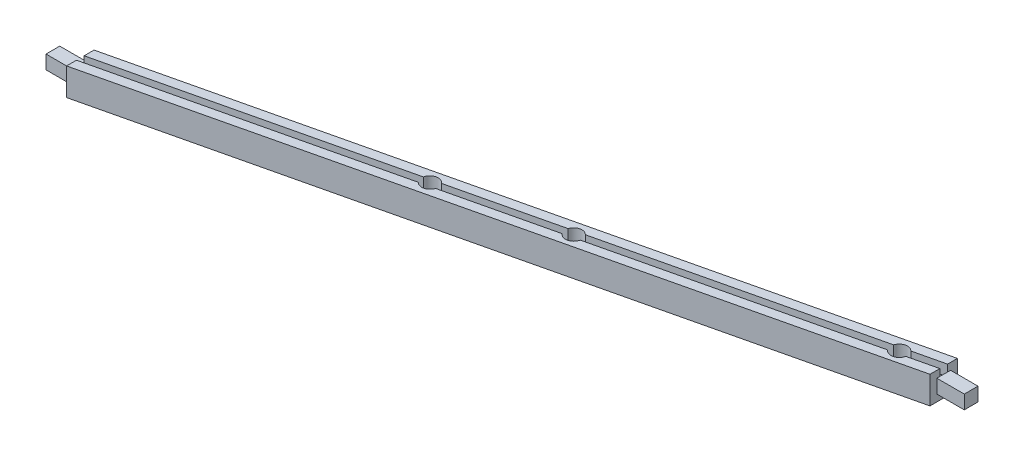
SolidWorks part; units mm, degrees
ref_plane "Front Plane" through (0, 0, 0) normal (0, 0, 1) x (1, 0, 0)
ref_plane "Top Plane" through (0, 0, 0) normal (0, 1, 0) x (1, 0, 0)
ref_plane "Right Plane" through (0, 0, 0) normal (1, 0, 0) x (0, 0, -1)
sketch "Sketch1" plane through (0, 0, 0) normal (0, 1, 0) x (1, 0, 0)
  line L0 (0, 0) -> (127.3, 30)
  line L1 (0, 0) -> (127.3, 0)
  line L2 (0, 0) -> (0, 35)
  line L3 (0, 35) -> (127.3, 35)
  line L4 (127.3, 0) -> (127.3, 35)
  line L5 (127.3, 35) -> (0, 5)
  dimension "D1" = 35
  dimension "D2" = 127.3
  dimension "D3" = 5
  dimension "D4" = 5
extrude "Boss-Extrude1" add sketch "Sketch1" along normal blind 5 contours L4 L5 L2 L0
sketch "Sketch2" plane through (127.3, 0, 0) normal (1, 0, 0) x (0, 0, -1)
  line L0 (30, 5) -> (30, 0) construction
  line L1 (31.25, 3.75) -> (33.75, 3.75)
  line L2 (31.25, 3.75) -> (31.25, 1.25)
  line L3 (31.25, 1.25) -> (33.75, 1.25)
  line L4 (33.75, 3.75) -> (33.75, 1.25)
  line L5 (30, 5) -> (35, 5) construction
  dimension "D1" = 2.5
  dimension "D2" = 2.5
  dimension "D3" = 1.25
  dimension "D4" = 1.25
extrude "Boss-Extrude2" add sketch "Sketch2" along normal blind 5
sketch "Sketch3" plane through (0, 0, 0) normal (-1, 0, 0) x (0, 0, 1)
  line L0 (0, 0) -> (-5, 0) construction
  line L1 (-3.75, 3.75) -> (-1.25, 3.75)
  line L2 (-3.75, 3.75) -> (-3.75, 1.25)
  line L3 (-3.75, 1.25) -> (-1.25, 1.25)
  line L4 (-1.25, 3.75) -> (-1.25, 1.25)
  line L5 (0, 5) -> (0, 0) construction
  dimension "D1" = 2.5
  dimension "D2" = 2.5
  dimension "D3" = 1.25
  dimension "D4" = 1.25
extrude "Boss-Extrude3" add sketch "Sketch3" along normal blind 5
sketch "Sketch6" plane through (0, 0, 0) normal (0, -1, 0) x (1, 0, 0)
  line L0 (0, 0) -> (127.3, -30) construction
  line L1 (0, 0) -> (0, -5) construction
  line L2 (127.3, -35) -> (0, -5) construction
  line L3 (127.3, -30) -> (127.3, -35) construction
  circle A0 centre (51.5, -14.7052) radius 1.5
  circle A1 centre (72.8, -19.5878) radius 1.5
  circle A2 centre (120.8, -30.8997) radius 1.5
  dimension "D1" = 3
  dimension "D2" = 2.5
  dimension "D3" = 51.5
  dimension "D4" = 3
  dimension "D5" = 2.5
  dimension "D6" = 6.5
  dimension "D7" = 48
  dimension "D8" = 2.5
  dimension "D9" = 3
extrude "Cut-Extrude1" cut sketch "Sketch6" against normal blind 5
sketch "Sketch10" plane through (0, 5, 0) normal (0, 1, 0) x (1, 0, 0)
  line L0 (0, 3.2021) -> (0, 1.7979)
  line L1 (0, 0) -> (0, 5) construction
  line L2 (0, 1.7979) -> (127.3, 31.7979)
  line L3 (127.3, 30) -> (127.3, 35) construction
  line L4 (127.3, 31.7979) -> (127.3, 33.2021)
  line L5 (127.3, 33.2021) -> (0, 3.2021)
  line L6 (127.3, 35) -> (0, 5) construction
  line L7 (0, 0) -> (127.3, 30) construction
  dimension "D1" = 1.75
  dimension "D2" = 1.75
  dimension "D3" = 1.75
  dimension "D4" = 1.75
extrude "Cut-Extrude3" cut sketch "Sketch10" against normal blind 2
